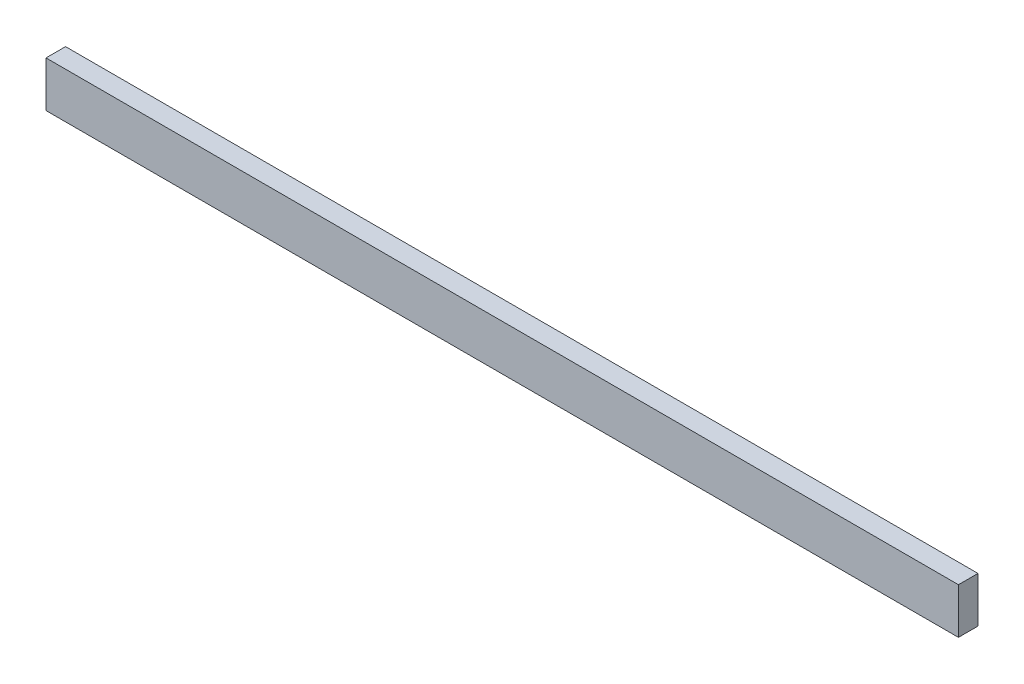
SolidWorks part; units mm, degrees
material "Pine"
ref_plane "Front Plane" through (0, 0, 0) normal (0, 0, 1) x (1, 0, 0)
ref_plane "Top Plane" through (0, 0, 0) normal (0, 1, 0) x (1, 0, 0)
ref_plane "Right Plane" through (0, 0, 0) normal (1, 0, 0) x (0, 0, -1)
sketch "Sketch1" plane through (0, 0, 0) normal (1, 0, 0) x (0, 0, -1)
  line L1 (0, 0) -> (38.1, 0)
  line L2 (0, 0) -> (0, 88.9)
  line L3 (0, 88.9) -> (38.1, 88.9)
  line L4 (38.1, 0) -> (38.1, 88.9)
  dimension "D1" = 38.1
  dimension "D2" = 88.9
extrude "Boss-Extrude1" add sketch "Sketch1" along normal blind 1778
